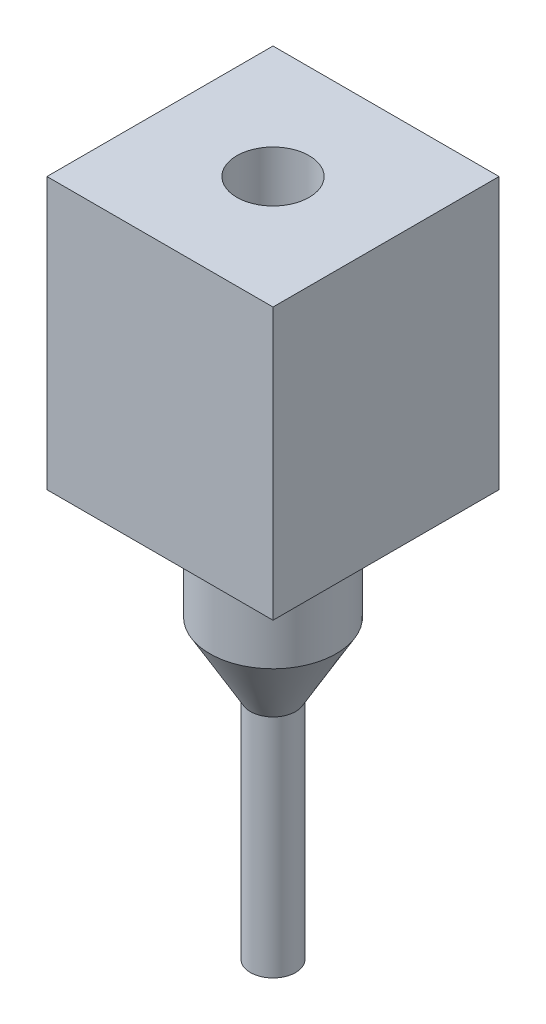
SolidWorks part; units mm, degrees
ref_plane "Спереди" through (0, 0, 0) normal (0, 0, 1) x (1, 0, 0)
ref_plane "Сверху" through (0, 0, 0) normal (0, 1, 0) x (1, 0, 0)
ref_plane "Справа" through (0, 0, 0) normal (1, 0, 0) x (0, 0, -1)
sketch "Эскиз1" plane through (0, 0, 0) normal (0, 1, 0) x (1, 0, 0)
  line L1 (1.25, 1.25) -> (-1.25, 1.25)
  line L2 (1.25, 1.25) -> (1.25, -1.25)
  line L3 (1.25, -1.25) -> (-1.25, -1.25)
  line L4 (-1.25, 1.25) -> (-1.25, -1.25)
  line L5 (1.25, 1.25) -> (-1.25, -1.25) construction
  line L6 (1.25, -1.25) -> (-1.25, 1.25) construction
  point P0 (0, 0)
  dimension "D1" = 2.5
extrude "Бобышка-Вытянуть1" add sketch "Эскиз1" along normal blind 3
sketch "Эскиз2" plane through (0, 0, 0) normal (0, -1, 0) x (1, 0, 0)
  circle A0 centre (0, 0) radius 0.7
  dimension "D1" = 1.4
extrude "Бобышка-Вытянуть2" add sketch "Эскиз2" along normal blind 2
chamfer "Фаска1" distance 0.7794 angle 30 1 edges at (0, -2, -0.7)
sketch "Эскиз3" plane through (0, -2, 0) normal (0, -1, 0) x (1, 0, 0)
  circle A1 centre (0, 0) radius 0.25
  circle A2 centre (0, 0) radius 0.25
  dimension "D1" = 0
extrude "Бобышка-Вытянуть3" add sketch "Эскиз3" along normal blind 2.5
sketch "Эскиз4" plane through (0, 3, 0) normal (0, 1, 0) x (1, 0, 0)
  circle A0 centre (0, 0) radius 0.4
  dimension "D1" = 0.8
extrude "Вырез-Вытянуть1" cut sketch "Эскиз4" against normal blind 2.5
